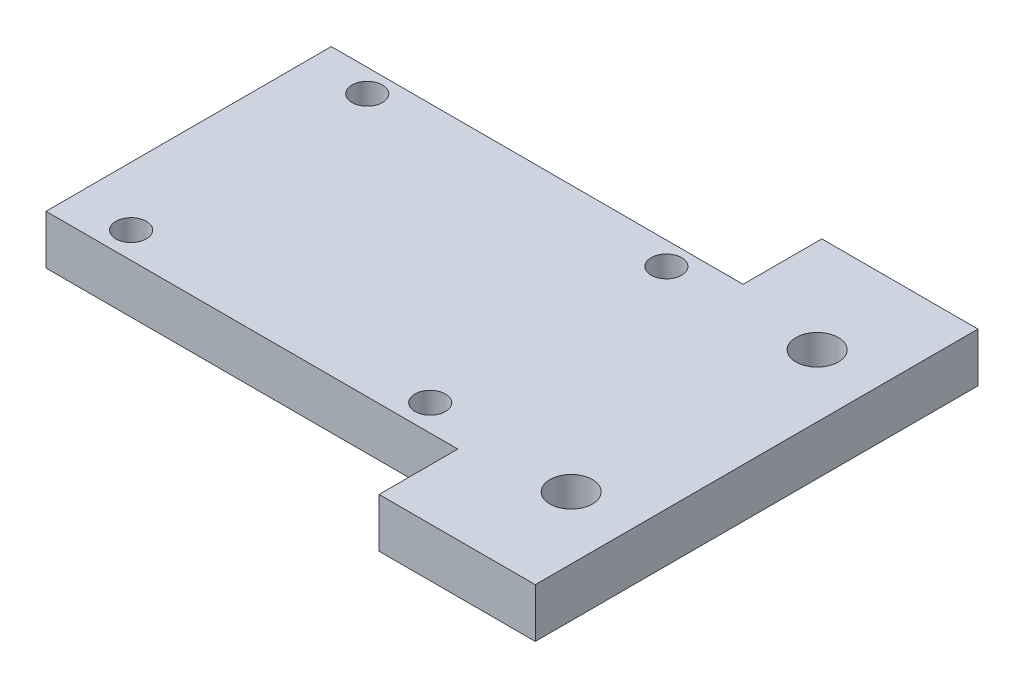
SolidWorks part; units mm, degrees
material "ABS"
ref_plane "Front Plane" through (0, 0, 0) normal (0, 0, 1) x (1, 0, 0)
ref_plane "Top Plane" through (0, 0, 0) normal (0, 1, 0) x (1, 0, 0)
ref_plane "Right Plane" through (0, 0, 0) normal (1, 0, 0) x (0, 0, -1)
sketch "Sketch1" plane through (0, 0, 0) normal (0, 1, 0) x (1, 0, 0)
  line L0 (-21.1827, -16.674) -> (36.55, -16.674) construction
  line L1 (30.2, -29.174) -> (30.2, -4.174) construction
  line L16 (36.55, 27.1492) -> (36.55, -43.6508)
  line L17 (20.675, -43.6508) -> (36.55, -43.6508)
  line L18 (20.675, -31.174) -> (20.675, -43.6508)
  line L19 (20.675, -31.174) -> (-21.1827, -31.174)
  line L20 (-21.1827, -31.174) -> (-21.1827, -2.174)
  line L21 (-21.1827, -31.174) -> (20.675, -2.174) construction
  line L22 (-21.1827, -2.174) -> (20.675, -31.174) construction
  line L23 (-21.1827, -2.174) -> (20.675, -2.174)
  line L25 (20.675, 27.1492) -> (36.55, 27.1492)
  line L26 (20.675, -2.174) -> (20.675, 27.1492)
  circle A6 centre (30.2, -29.174) radius 2.159
  circle A7 centre (-15.2, -28.5016) radius 1.55
  circle A8 centre (15.2, -28.5016) radius 1.55
  circle A9 centre (-15.2, -4.5016) radius 1.55
  circle A10 centre (15.2, -4.5016) radius 1.55
  circle A11 centre (30.2, -4.174) radius 2.159
  point P2 (30.2, -16.674)
  point P3 (0, 0)
  dimension "D3" = 4.318
  dimension "D4" = 14.4768
  dimension "D5" = 15.875
  dimension "D2" = 4.318
  dimension "D1" = 25
  dimension "D6" = 15.875
  dimension "D7" = 41.8577
  dimension "D8" = 30.4
extrude "Boss-Extrude1" add sketch "Sketch1" along normal blind 5
sketch "Sketch2" plane through (0, 5, 0) normal (0, 1, 0) x (1, 0, 0)
  line L1 (12.6933, -52.1871) -> (45.4209, -52.1871)
  line L2 (12.6933, -52.1871) -> (12.6933, -39.174)
  line L3 (12.6933, -39.174) -> (45.4209, -39.174)
  line L4 (45.4209, -52.1871) -> (45.4209, -39.174)
  line L5 (12.6933, 5.826) -> (52.1061, 5.826)
  line L6 (12.6933, 5.826) -> (12.6933, 30.3004)
  line L7 (12.6933, 30.3004) -> (52.1061, 30.3004)
  line L8 (52.1061, 5.826) -> (52.1061, 30.3004)
  circle A0 centre (30.2, -29.174) radius 2.159 construction
  circle A1 centre (30.2, -4.174) radius 2.159 construction
  dimension "D1" = 10
  dimension "D2" = 10
extrude "Cut-Extrude1" cut sketch "Sketch2" against normal through all
